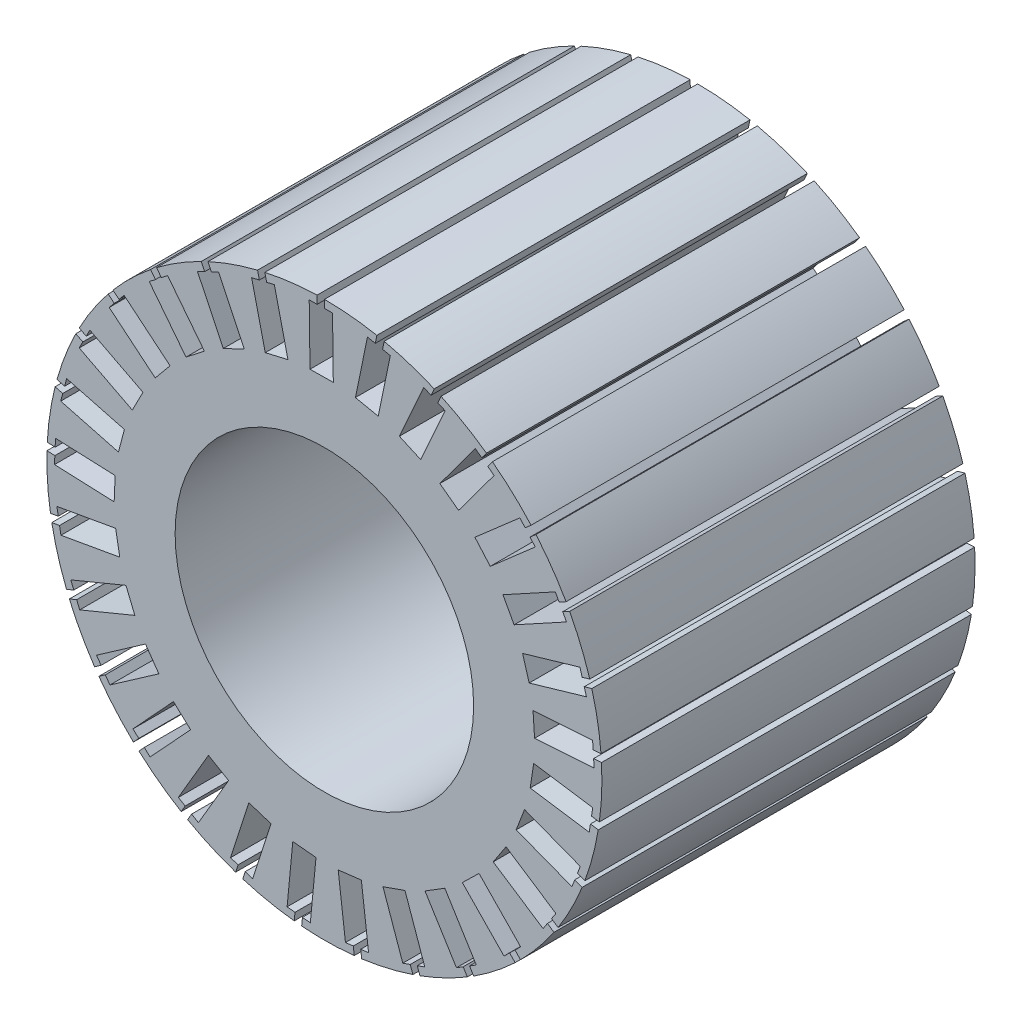
SolidWorks part; units mm, degrees
ref_plane "Спереди" through (0, 0, 0) normal (0, 0, 1) x (1, 0, 0)
ref_plane "Сверху" through (0, 0, 0) normal (0, 1, 0) x (1, 0, 0)
ref_plane "Справа" through (0, 0, 0) normal (1, 0, 0) x (0, 0, -1)
sketch "Эскиз1" plane through (0, 0, 0) normal (0, 0, 1) x (1, 0, 0)
  circle A0 centre (0, 0) radius 29.75
  circle A1 centre (0, 0) radius 16
extrude "Rotor_stack" add sketch "Эскиз1" along normal blind 40 from offset 20
sketch "Эскиз2" plane through (0, 0, 0) normal (0, 0, 1) x (1, 0, 0)
  line L0 (30.7049, 1.6645) -> (28.8617, 1.5405)
  line L1 (28.8617, 1.5405) -> (28.9187, 0.6924)
  line L2 (28.9187, 0.6924) -> (22.5332, 0.2629)
  line L3 (22.5332, 0.2629) -> (22.3654, 2.7573)
  line L4 (22.3654, 2.7573) -> (28.7509, 3.1868)
  line L5 (28.7509, 3.1868) -> (28.808, 2.3387)
  line L6 (28.808, 2.3387) -> (30.6512, 2.4627)
  line L7 (30.6512, 2.4627) -> (30.7049, 1.6645)
  line L8 (29.6292, 8.2262) -> (27.8557, 7.7089)
  line L9 (27.8557, 7.7089) -> (28.0938, 6.8929)
  line L10 (28.0938, 6.8929) -> (21.9498, 5.1007)
  line L11 (21.9498, 5.1007) -> (21.2498, 7.5007)
  line L12 (21.2498, 7.5007) -> (27.3937, 9.2929)
  line L13 (27.3937, 9.2929) -> (27.6317, 8.4769)
  line L14 (27.6317, 8.4769) -> (29.4052, 8.9942)
  line L15 (29.4052, 8.9942) -> (29.6292, 8.2262)
  line L16 (27.1681, 14.4033) -> (25.5473, 13.5168)
  line L17 (25.5473, 13.5168) -> (25.9552, 12.7711)
  line L18 (25.9552, 12.7711) -> (20.3402, 9.7)
  line L19 (20.3402, 9.7) -> (19.1405, 11.8934)
  line L20 (19.1405, 11.8934) -> (24.7556, 14.9645)
  line L21 (24.7556, 14.9645) -> (25.1634, 14.2187)
  line L22 (25.1634, 14.2187) -> (26.7842, 15.1052)
  line L23 (26.7842, 15.1052) -> (27.1681, 14.4033)
  line L24 (23.4367, 19.9069) -> (22.0443, 18.6927)
  line L25 (22.0443, 18.6927) -> (22.603, 18.0521)
  line L26 (22.603, 18.0521) -> (17.7794, 13.8458)
  line L27 (17.7794, 13.8458) -> (16.1363, 15.73)
  line L28 (16.1363, 15.73) -> (20.9599, 19.9363)
  line L29 (20.9599, 19.9363) -> (21.5185, 19.2957)
  line L30 (21.5185, 19.2957) -> (22.9109, 20.5099)
  line L31 (22.9109, 20.5099) -> (23.4367, 19.9069)
  line L32 (18.6093, 24.4797) -> (17.5105, 22.9946)
  line L33 (17.5105, 22.9946) -> (18.1938, 22.489)
  line L34 (18.1938, 22.489) -> (14.3873, 17.3441)
  line L35 (14.3873, 17.3441) -> (12.3776, 18.8311)
  line L36 (12.3776, 18.8311) -> (16.1841, 23.976)
  line L37 (16.1841, 23.976) -> (16.8674, 23.4704)
  line L38 (16.8674, 23.4704) -> (17.9662, 24.9555)
  line L39 (17.9662, 24.9555) -> (18.6093, 24.4797)
  line L40 (12.9118, 27.9078) -> (12.158, 26.2212)
  line L41 (12.158, 26.2212) -> (12.934, 25.8744)
  line L42 (12.934, 25.8744) -> (10.3225, 20.0315)
  line L43 (10.3225, 20.0315) -> (8.0401, 21.0516)
  line L44 (8.0401, 21.0516) -> (10.6516, 26.8945)
  line L45 (10.6516, 26.8945) -> (11.4276, 26.5477)
  line L46 (11.4276, 26.5477) -> (12.1815, 28.2343)
  line L47 (12.1815, 28.2343) -> (12.9118, 27.9078)
  line L48 (6.6106, 30.031) -> (6.237, 28.2218)
  line L49 (6.237, 28.2218) -> (7.0694, 28.0499)
  line L50 (7.0694, 28.0499) -> (5.7749, 21.7822)
  line L51 (5.7749, 21.7822) -> (3.3266, 22.2878)
  line L52 (3.3266, 22.2878) -> (4.6211, 28.5555)
  line L53 (4.6211, 28.5555) -> (5.4535, 28.3836)
  line L54 (5.4535, 28.3836) -> (5.8271, 30.1928)
  line L55 (5.8271, 30.1928) -> (6.6106, 30.031)
  line L56 (0.0003, 30.75) -> (0.0243, 28.9028)
  line L57 (0.0243, 28.9028) -> (0.8742, 28.9138)
  line L58 (0.8742, 28.9138) -> (0.9574, 22.5143)
  line L59 (0.9574, 22.5143) -> (-1.5424, 22.4818)
  line L60 (-1.5424, 22.4818) -> (-1.6256, 28.8813)
  line L61 (-1.6256, 28.8813) -> (-0.7756, 28.8924)
  line L62 (-0.7756, 28.8924) -> (-0.7997, 30.7396)
  line L63 (-0.7997, 30.7396) -> (0.0003, 30.75)
  line L64 (-6.6101, 30.0311) -> (-6.1895, 28.2322)
  line L65 (-6.1895, 28.2322) -> (-5.3618, 28.4257)
  line L66 (-5.3618, 28.4257) -> (-3.9049, 22.1938)
  line L67 (-3.9049, 22.1938) -> (-6.3393, 21.6247)
  line L68 (-6.3393, 21.6247) -> (-7.7962, 27.8566)
  line L69 (-7.7962, 27.8566) -> (-6.9685, 28.0501)
  line L70 (-6.9685, 28.0501) -> (-7.3891, 29.849)
  line L71 (-7.3891, 29.849) -> (-6.6101, 30.0311)
  line L72 (-12.9113, 27.9081) -> (-12.1139, 26.2416)
  line L73 (-12.1139, 26.2416) -> (-11.3472, 26.6085)
  line L74 (-11.3472, 26.6085) -> (-8.5846, 20.8355)
  line L75 (-8.5846, 20.8355) -> (-10.8397, 19.7563)
  line L76 (-10.8397, 19.7563) -> (-13.6023, 25.5294)
  line L77 (-13.6023, 25.5294) -> (-12.8355, 25.8963)
  line L78 (-12.8355, 25.8963) -> (-13.633, 27.5627)
  line L79 (-13.633, 27.5627) -> (-12.9113, 27.9081)
  line L80 (-18.6089, 24.48) -> (-17.4719, 23.024)
  line L81 (-17.4719, 23.024) -> (-16.8019, 23.5471)
  line L82 (-16.8019, 23.5471) -> (-12.8629, 18.5029)
  line L83 (-12.8629, 18.5029) -> (-14.8333, 16.9642)
  line L84 (-14.8333, 16.9642) -> (-18.7723, 22.0085)
  line L85 (-18.7723, 22.0085) -> (-18.1024, 22.5316)
  line L86 (-18.1024, 22.5316) -> (-19.2394, 23.9876)
  line L87 (-19.2394, 23.9876) -> (-18.6089, 24.48)
  line L88 (-23.4363, 19.9073) -> (-22.0129, 18.7298)
  line L89 (-22.0129, 18.7298) -> (-21.4711, 19.3847)
  line L90 (-21.4711, 19.3847) -> (-16.5398, 15.3052)
  line L91 (-16.5398, 15.3052) -> (-18.1333, 13.3789)
  line L92 (-18.1333, 13.3789) -> (-23.0646, 17.4584)
  line L93 (-23.0646, 17.4584) -> (-22.5228, 18.1133)
  line L94 (-22.5228, 18.1133) -> (-23.9462, 19.2909)
  line L95 (-23.9462, 19.2909) -> (-23.4363, 19.9073)
  line L96 (-27.1679, 14.4038) -> (-25.5246, 13.5598)
  line L97 (-25.5246, 13.5598) -> (-25.1362, 14.3158)
  line L98 (-25.1362, 14.3158) -> (-19.4432, 11.3918)
  line L99 (-19.4432, 11.3918) -> (-20.5854, 9.168)
  line L100 (-20.5854, 9.168) -> (-26.2784, 12.092)
  line L101 (-26.2784, 12.092) -> (-25.8901, 12.8481)
  line L102 (-25.8901, 12.8481) -> (-27.5334, 13.6922)
  line L103 (-27.5334, 13.6922) -> (-27.1679, 14.4038)
  line L104 (-29.6291, 8.2268) -> (-27.8428, 7.7557)
  line L105 (-27.8428, 7.7557) -> (-27.626, 8.5776)
  line L106 (-27.626, 8.5776) -> (-21.4376, 6.9457)
  line L107 (-21.4376, 6.9457) -> (-22.075, 4.5284)
  line L108 (-22.075, 4.5284) -> (-28.2635, 6.1602)
  line L109 (-28.2635, 6.1602) -> (-28.0467, 6.9822)
  line L110 (-28.0467, 6.9822) -> (-29.8331, 7.4532)
  line L111 (-29.8331, 7.4532) -> (-29.6291, 8.2268)
  line L112 (-30.7049, 1.665) -> (-28.8591, 1.589)
  line L113 (-28.8591, 1.589) -> (-28.8241, 2.4383)
  line L114 (-28.8241, 2.4383) -> (-22.4295, 2.1749)
  line L115 (-22.4295, 2.1749) -> (-22.5324, -0.323)
  line L116 (-22.5324, -0.323) -> (-28.927, -0.0596)
  line L117 (-28.927, -0.0596) -> (-28.892, 0.7897)
  line L118 (-28.892, 0.7897) -> (-30.7378, 0.8657)
  line L119 (-30.7378, 0.8657) -> (-30.7049, 1.665)
  line L120 (-30.345, -4.9745) -> (-28.5259, -4.652)
  line L121 (-28.5259, -4.652) -> (-28.6743, -3.815)
  line L122 (-28.6743, -3.815) -> (-22.3726, -2.6976)
  line L123 (-22.3726, -2.6976) -> (-21.9362, -5.1592)
  line L124 (-21.9362, -5.1592) -> (-28.2379, -6.2766)
  line L125 (-28.2379, -6.2766) -> (-28.3863, -5.4397)
  line L126 (-28.3863, -5.4397) -> (-30.2053, -5.7622)
  line L127 (-30.2053, -5.7622) -> (-30.345, -4.9745)
  line L128 (-28.5661, -11.3815) -> (-26.859, -10.6755)
  line L129 (-26.859, -10.6755) -> (-27.1838, -9.89)
  line L130 (-27.1838, -9.89) -> (-21.2697, -7.444)
  line L131 (-21.2697, -7.444) -> (-20.3142, -9.7542)
  line L132 (-20.3142, -9.7542) -> (-26.2284, -12.2002)
  line L133 (-26.2284, -12.2002) -> (-26.5532, -11.4147)
  line L134 (-26.5532, -11.4147) -> (-28.2604, -12.1208)
  line L135 (-28.2604, -12.1208) -> (-28.5661, -11.3815)
  line L136 (-25.4516, -17.2563) -> (-23.9361, -16.1998)
  line L137 (-23.9361, -16.1998) -> (-24.4222, -15.5025)
  line L138 (-24.4222, -15.5025) -> (-19.1722, -11.8423)
  line L139 (-19.1722, -11.8423) -> (-17.7424, -13.8931)
  line L140 (-17.7424, -13.8931) -> (-22.9925, -17.5533)
  line L141 (-22.9925, -17.5533) -> (-23.4786, -16.856)
  line L142 (-23.4786, -16.856) -> (-24.9941, -17.9125)
  line L143 (-24.9941, -17.9125) -> (-25.4516, -17.2563)
  line L144 (-21.147, -22.3242) -> (-19.894, -20.9666)
  line L145 (-19.894, -20.9666) -> (-20.5187, -20.3901)
  line L146 (-20.5187, -20.3901) -> (-16.1782, -15.6869)
  line L147 (-16.1782, -15.6869) -> (-14.341, -17.3824)
  line L148 (-14.341, -17.3824) -> (-18.6815, -22.0856)
  line L149 (-18.6815, -22.0856) -> (-19.3061, -21.5091)
  line L150 (-19.3061, -21.5091) -> (-20.5591, -22.8667)
  line L151 (-20.5591, -22.8667) -> (-21.147, -22.3242)
  line L152 (-15.8535, -26.3482) -> (-14.9217, -24.753)
  line L153 (-14.9217, -24.753) -> (-15.6557, -24.3243)
  line L154 (-15.6557, -24.3243) -> (-12.4277, -18.798)
  line L155 (-12.4277, -18.798) -> (-10.269, -20.0589)
  line L156 (-10.269, -20.0589) -> (-13.497, -25.5852)
  line L157 (-13.497, -25.5852) -> (-14.2309, -25.1565)
  line L158 (-14.2309, -25.1565) -> (-15.1627, -26.7517)
  line L159 (-15.1627, -26.7517) -> (-15.8535, -26.3482)
  line L160 (-9.8188, -29.1402) -> (-9.2517, -27.382)
  line L161 (-9.2517, -27.382) -> (-10.0607, -27.1211)
  line L162 (-10.0607, -27.1211) -> (-8.0962, -21.0301)
  line L163 (-8.0962, -21.0301) -> (-5.7168, -21.7975)
  line L164 (-5.7168, -21.7975) -> (-7.6814, -27.8885)
  line L165 (-7.6814, -27.8885) -> (-8.4903, -27.6276)
  line L166 (-8.4903, -27.6276) -> (-9.0574, -29.3858)
  line L167 (-9.0574, -29.3858) -> (-9.8188, -29.1402)
  line L168 (-3.3249, -30.5697) -> (-3.1491, -28.7307)
  line L169 (-3.1491, -28.7307) -> (-3.9952, -28.6498)
  line L170 (-3.9952, -28.6498) -> (-3.386, -22.2789)
  line L171 (-3.386, -22.2789) -> (-0.8974, -22.5168)
  line L172 (-0.8974, -22.5168) -> (-1.5066, -28.8878)
  line L173 (-1.5066, -28.8878) -> (-2.3527, -28.8069)
  line L174 (-2.3527, -28.8069) -> (-2.5286, -30.6459)
  line L175 (-2.5286, -30.6459) -> (-3.3249, -30.5697)
  line L176 (3.3244, -30.5698) -> (3.1008, -28.736)
  line L177 (3.1008, -28.736) -> (2.257, -28.8388)
  line L178 (2.257, -28.8388) -> (1.4824, -22.4859)
  line L179 (1.4824, -22.4859) -> (3.9641, -22.1833)
  line L180 (3.9641, -22.1833) -> (4.7387, -28.5362)
  line L181 (4.7387, -28.5362) -> (3.8949, -28.6391)
  line L182 (3.8949, -28.6391) -> (4.1185, -30.4729)
  line L183 (4.1185, -30.4729) -> (3.3244, -30.5698)
  line L184 (9.8183, -29.1404) -> (9.2057, -27.3975)
  line L185 (9.2057, -27.3975) -> (8.4038, -27.6794)
  line L186 (8.4038, -27.6794) -> (6.2816, -21.6415)
  line L187 (6.2816, -21.6415) -> (8.6401, -20.8125)
  line L188 (8.6401, -20.8125) -> (10.7623, -26.8504)
  line L189 (10.7623, -26.8504) -> (9.9604, -27.1323)
  line L190 (9.9604, -27.1323) -> (10.573, -28.8751)
  line L191 (10.573, -28.8751) -> (9.8183, -29.1404)
  line L192 (15.853, -26.3485) -> (14.8801, -24.7781)
  line L193 (14.8801, -24.7781) -> (14.1575, -25.2257)
  line L194 (14.1575, -25.2257) -> (10.787, -19.7852)
  line L195 (10.787, -19.7852) -> (12.9122, -18.4686)
  line L196 (12.9122, -18.4686) -> (16.2828, -23.9091)
  line L197 (16.2828, -23.9091) -> (15.5602, -24.3567)
  line L198 (15.5602, -24.3567) -> (16.5331, -25.9272)
  line L199 (16.5331, -25.9272) -> (15.853, -26.3485)
  line L200 (21.1466, -22.3245) -> (19.8588, -21)
  line L201 (19.8588, -21) -> (19.2493, -21.5925)
  line L202 (19.2493, -21.5925) -> (14.788, -17.0037)
  line L203 (14.788, -17.0037) -> (16.5805, -15.261)
  line L204 (16.5805, -15.261) -> (21.0418, -19.8498)
  line L205 (21.0418, -19.8498) -> (20.4324, -20.4423)
  line L206 (20.4324, -20.4423) -> (21.7202, -21.7669)
  line L207 (21.7202, -21.7669) -> (21.1466, -22.3245)
  line L208 (25.4513, -17.2567) -> (23.9089, -16.24)
  line L209 (23.9089, -16.24) -> (23.441, -16.9496)
  line L210 (23.441, -16.9496) -> (18.0976, -13.4272)
  line L211 (18.0976, -13.4272) -> (19.4735, -11.3399)
  line L212 (19.4735, -11.3399) -> (24.817, -14.8623)
  line L213 (24.817, -14.8623) -> (24.3492, -15.572)
  line L214 (24.3492, -15.572) -> (25.8916, -16.5888)
  line L215 (25.8916, -16.5888) -> (25.4513, -17.2567)
  line L216 (28.5659, -11.382) -> (26.841, -10.7206)
  line L217 (26.841, -10.7206) -> (26.5367, -11.5142)
  line L218 (26.5367, -11.5142) -> (20.5609, -9.2228)
  line L219 (20.5609, -9.2228) -> (21.456, -6.8886)
  line L220 (21.456, -6.8886) -> (27.4318, -9.18)
  line L221 (27.4318, -9.18) -> (27.1274, -9.9736)
  line L222 (27.1274, -9.9736) -> (28.8524, -10.635)
  line L223 (28.8524, -10.635) -> (28.5659, -11.382)
  line L224 (30.3449, -4.9751) -> (28.5181, -4.6999)
  line L225 (28.5181, -4.6999) -> (28.3915, -5.5404)
  line L226 (28.3915, -5.5404) -> (22.0629, -4.5872)
  line L227 (22.0629, -4.5872) -> (22.4352, -2.1151)
  line L228 (22.4352, -2.1151) -> (28.7638, -3.0683)
  line L229 (28.7638, -3.0683) -> (28.6372, -3.9088)
  line L230 (28.6372, -3.9088) -> (30.464, -4.184)
  line L231 (30.464, -4.184) -> (30.3449, -4.9751)
extrude "Rotor_slots" cut sketch "Эскиз2" against normal mid plane 42
